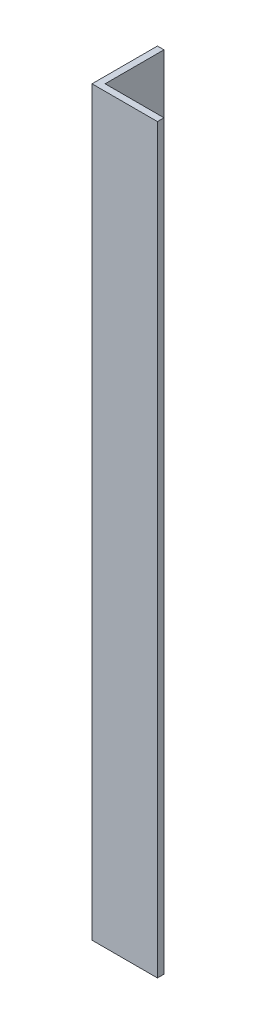
SolidWorks part; units mm, degrees
material "ASTM A36 Steel"
ref_plane "Front Plane" through (0, 0, 0) normal (0, 0, 1) x (1, 0, 0)
ref_plane "Top Plane" through (0, 0, 0) normal (0, 1, 0) x (1, 0, 0)
ref_plane "Right Plane" through (0, 0, 0) normal (1, 0, 0) x (0, 0, -1)
sketch "Sketch1" plane through (0, 0, 0) normal (0, 1, 0) x (1, 0, 0)
  line L0 (0, 0) -> (30, 0)
  line L1 (30, 0) -> (30, 3)
  line L2 (30, 3) -> (3, 3)
  line L3 (3, 3) -> (3, 30)
  line L4 (3, 30) -> (0, 30)
  line L5 (0, 30) -> (0, 0)
extrude "Boss-Extrude1" add sketch "Sketch1" along normal blind 340
